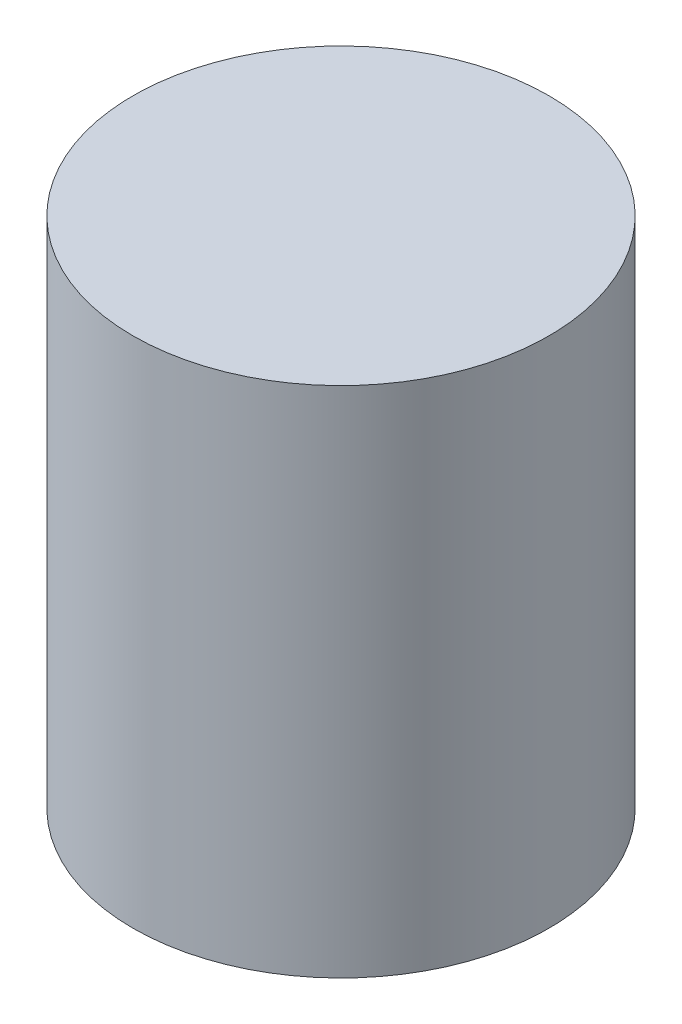
SolidWorks part; units mm, degrees
ref_plane "Ön Düzlem" through (0, 0, 0) normal (0, 0, 1) x (1, 0, 0)
ref_plane "Üst Düzlem" through (0, 0, 0) normal (0, 1, 0) x (1, 0, 0)
ref_plane "Sağ Düzlem" through (0, 0, 0) normal (1, 0, 0) x (0, 0, -1)
sketch "Çizim1" plane through (0, 0, 0) normal (0, 1, 0) x (1, 0, 0)
  circle A0 centre (0, 0) radius 7.5
  dimension "D1" = 15
extrude "Yükseklik-Ekstrüzyon1" add sketch "Çizim1" along normal blind 18.5
